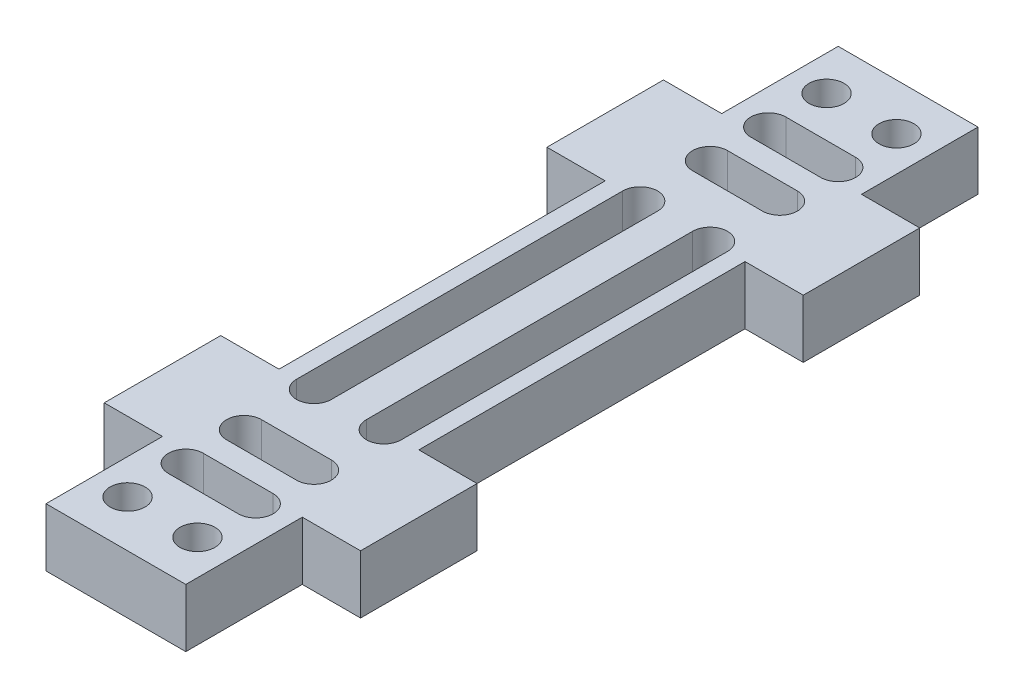
SolidWorks part; units mm, degrees
ref_plane "前视基准面" through (0, 0, 0) normal (0, 0, 1) x (1, 0, 0)
ref_plane "上视基准面" through (0, 0, 0) normal (0, 1, 0) x (1, 0, 0)
ref_plane "右视基准面" through (0, 0, 0) normal (1, 0, 0) x (0, 0, -1)
sketch "草图1" plane through (0, 0, 0) normal (0, 1, 0) x (1, 0, 0)
  line L0 (0, 0) -> (0, 10)
  line L1 (0, 10) -> (-5, 10)
  line L2 (-5, 10) -> (-5, 20)
  line L3 (-5, 20) -> (0, 20)
  line L4 (0, 20) -> (0, 48)
  line L5 (0, 48) -> (-5, 48)
  line L6 (-5, 48) -> (-5, 58)
  line L7 (-5, 58) -> (0, 58)
  line L8 (0, 58) -> (0, 68)
  line L9 (0, 68) -> (12, 68)
  line L10 (12, 68) -> (12, 58)
  line L11 (12, 58) -> (17, 58)
  line L12 (17, 58) -> (17, 48)
  line L13 (17, 48) -> (12, 48)
  line L14 (12, 48) -> (12, 20)
  line L15 (12, 20) -> (17, 20)
  line L16 (17, 20) -> (17, 10)
  line L17 (17, 10) -> (12, 10)
  line L18 (12, 10) -> (12, 0)
  line L19 (12, 0) -> (0, 0)
  line L20 (3, 76.6028) -> (3, -24.4459) construction
  line L21 (9, 76.6028) -> (9, -24.4459) construction
  line L22 (-1.5183, 54) -> (12, 54) construction
  line L23 (-1.5183, 14) -> (13.1568, 14) construction
  line L24 (3, 54) -> (9, 54) construction
  line L25 (3, 55.5) -> (9, 55.5)
  line L26 (3, 52.5) -> (9, 52.5)
  line L27 (3, 14) -> (9, 14) construction
  line L28 (3, 15.5) -> (9, 15.5)
  line L29 (3, 12.5) -> (9, 12.5)
  line L30 (3, 48) -> (3, 20) construction
  line L31 (4.5, 48) -> (4.5, 20)
  line L32 (1.5, 48) -> (1.5, 20)
  line L33 (9, 48) -> (9, 20) construction
  line L34 (10.5, 48) -> (10.5, 20)
  line L35 (7.5, 48) -> (7.5, 20)
  line L36 (-2.7762, 64) -> (13.1568, 64) construction
  line L37 (-2.7762, 4) -> (13.1568, 4) construction
  line L38 (1.5, 59) -> (10.5, 59) construction
  line L39 (1.5, 9) -> (10.5, 9) construction
  line L40 (3, 59) -> (9, 59) construction
  line L41 (3, 60.5) -> (9, 60.5)
  line L42 (3, 57.5) -> (9, 57.5)
  line L43 (3, 9) -> (9, 9) construction
  line L44 (3, 10.5) -> (9, 10.5)
  line L45 (3, 7.5) -> (9, 7.5)
  arc A0 (3, 55.5) -> (3, 52.5) centre (3, 54) ccw
  arc A1 (9, 52.5) -> (9, 55.5) centre (9, 54) ccw
  arc A2 (3, 15.5) -> (3, 12.5) centre (3, 14) ccw
  arc A3 (9, 12.5) -> (9, 15.5) centre (9, 14) ccw
  arc A4 (4.5, 48) -> (1.5, 48) centre (3, 48) ccw
  arc A5 (1.5, 20) -> (4.5, 20) centre (3, 20) ccw
  arc A6 (10.5, 48) -> (7.5, 48) centre (9, 48) ccw
  arc A7 (7.5, 20) -> (10.5, 20) centre (9, 20) ccw
  circle A8 centre (3, 64) radius 1.5
  circle A9 centre (9, 64) radius 1.5
  circle A10 centre (3, 4) radius 1.5
  circle A11 centre (9, 4) radius 1.5
  arc A12 (3, 60.5) -> (3, 57.5) centre (3, 59) ccw
  arc A13 (9, 57.5) -> (9, 60.5) centre (9, 59) ccw
  arc A14 (3, 10.5) -> (3, 7.5) centre (3, 9) ccw
  arc A15 (9, 7.5) -> (9, 10.5) centre (9, 9) ccw
  point P28 (14.5, 58)
  point P32 (6, 54)
  point P37 (6, 14)
  point P44 (3, 34)
  point P51 (9, 34)
  point P62 (6, 68)
  point P75 (6, 59)
  point P82 (6, 9)
  dimension "D1" = 68
  dimension "D22" = 4
  dimension "D24" = 28
  dimension "D28" = 6
  dimension "D2" = 12
  dimension "D3" = 5
  dimension "D4" = 5
  dimension "D5" = 10
  dimension "D6" = 10
  dimension "D7" = 10
  dimension "D8" = 10
  dimension "D9" = 5
  dimension "D10" = 5
  dimension "D11" = 10
  dimension "D12" = 10
  dimension "D13" = 10
  dimension "D14" = 10
  dimension "D15" = 5
  dimension "D16" = 5
  dimension "D17" = 3
  dimension "D18" = 3
  dimension "D19" = 4
  dimension "D20" = 4
  dimension "D21" = 40
  dimension "D23" = 4
  dimension "D25" = 28
  dimension "D26" = 5
  dimension "D27" = 5
extrude "凸台-拉伸1" add sketch "草图1" along normal blind 5
